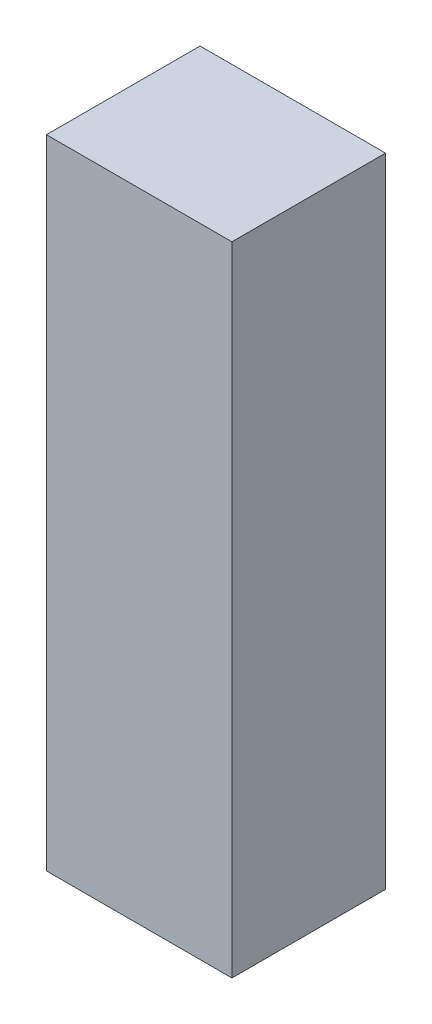
SolidWorks part; units mm, degrees
ref_plane "Plano frontal" through (0, 0, 0) normal (0, 0, 1) x (1, 0, 0)
ref_plane "Plano superior" through (0, 0, 0) normal (0, 1, 0) x (1, 0, 0)
ref_plane "Plano direito" through (0, 0, 0) normal (1, 0, 0) x (0, 0, -1)
sketch "Esboço1" plane through (0, 0, 0) normal (0, 0, 1) x (1, 0, 0)
  line L1 (16, 55) -> (-16, 55)
  line L2 (16, 55) -> (16, -55)
  line L3 (16, -55) -> (-16, -55)
  line L4 (-16, 55) -> (-16, -55)
  line L5 (16, 55) -> (-16, -55) construction
  line L6 (16, -55) -> (-16, 55) construction
  point P0 (0, 0)
  dimension "D1" = 110
  dimension "D2" = 32
extrude "Ressalto-extrusão1" add sketch "Esboço1" along normal blind 26.5
